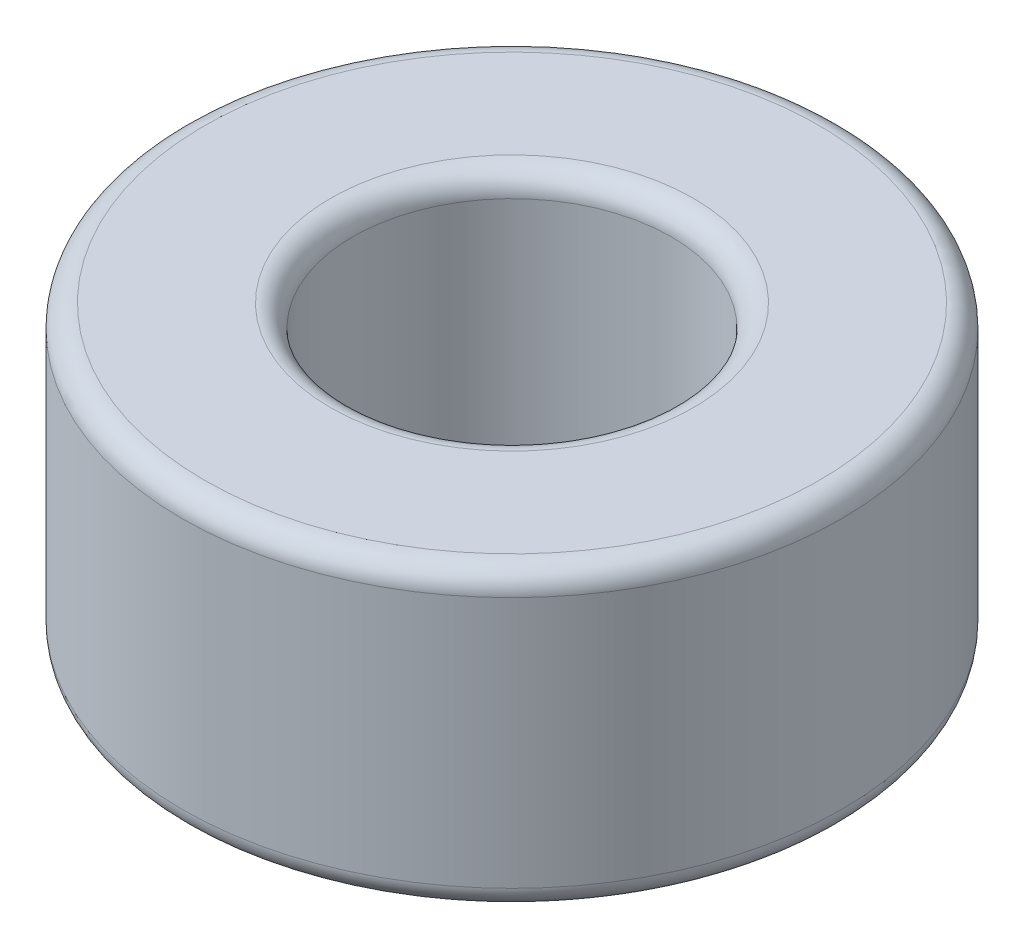
SolidWorks part; units mm, degrees
ref_plane "Спереди" through (0, 0, 0) normal (0, 0, 1) x (1, 0, 0)
ref_plane "Сверху" through (0, 0, 0) normal (0, 1, 0) x (1, 0, 0)
ref_plane "Справа" through (0, 0, 0) normal (1, 0, 0) x (0, 0, -1)
sketch "Эскиз1" plane through (0, 0, 0) normal (0, 1, 0) x (1, 0, 0)
  circle A0 centre (0, 0) radius 2.15
  circle A1 centre (0, 0) radius 4.45
  dimension "D1" = 4.3
  dimension "D2" = 8.9
extrude "Бобышка-Вытянуть1" add sketch "Эскиз1" along normal blind 4
fillet "Скругление1" radius 0.3 4 edges at (0, 0, 2.15) (0, 0, 4.45) (0, 4, 2.15) (0, 4, 4.45)
